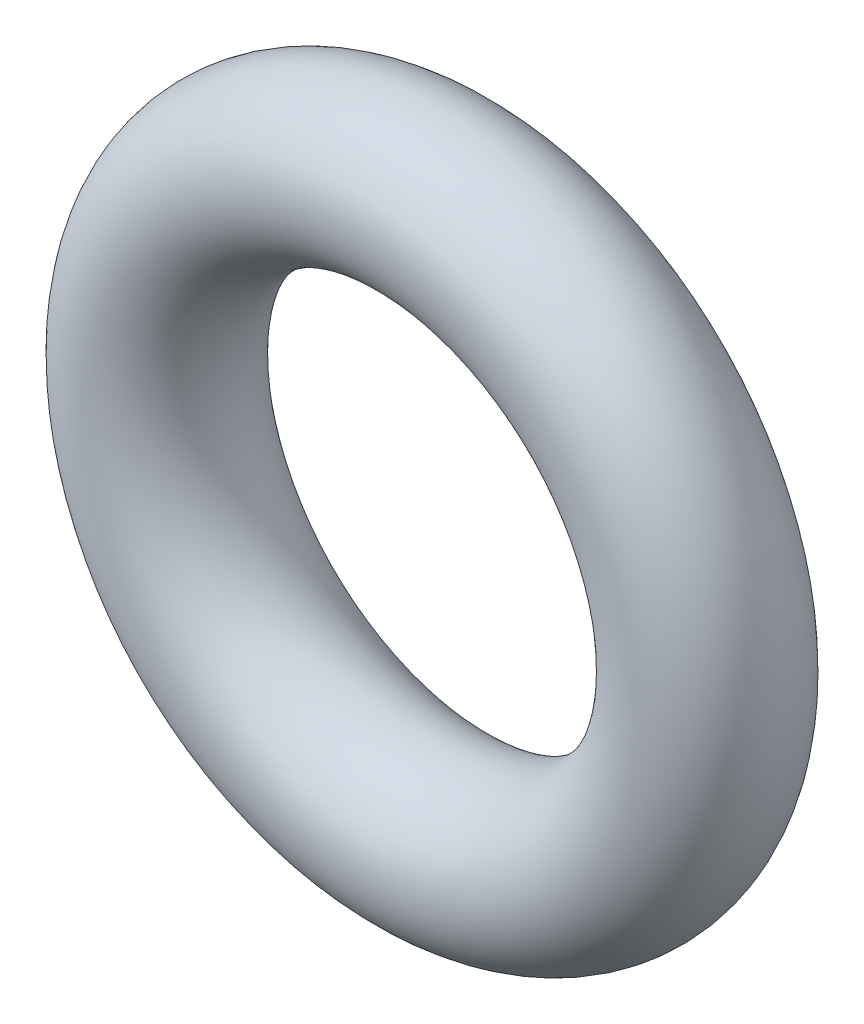
SolidWorks part; units mm, degrees
ref_plane "Front Plane" through (0, 0, 0) normal (0, 0, 1) x (1, 0, 0)
ref_plane "Top Plane" through (0, 0, 0) normal (0, 1, 0) x (1, 0, 0)
ref_plane "Right Plane" through (0, 0, 0) normal (1, 0, 0) x (0, 0, -1)
sketch "Sketch1" plane through (0, 0, 0) normal (0, 1, 0) x (1, 0, 0)
  line L0 (0, 0) -> (0, 11.5476) construction
  circle A0 centre (3.125, 0) radius 0.89
  point P5 (2.235, 0)
  point P6 (4.015, 0)
  dimension "D1" = 2.235
  dimension "D2" = 4.015
revolve "Revolve1" add sketch "Sketch1" angle 360 about L0
sketch "Sketch2" plane through (0, 0, 0) normal (0, 0, 1) x (1, 0, 0)
  circle A0 centre (0, 0) radius 2.235
  circle A1 centre (0, 0) radius 4.015
